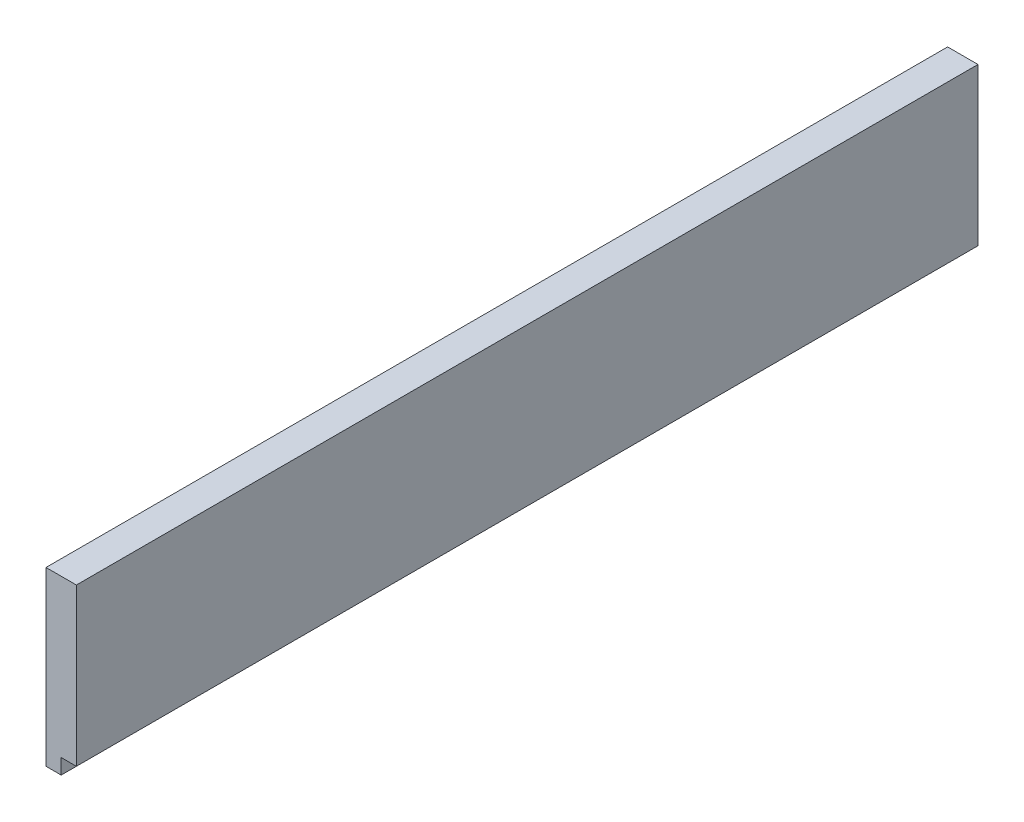
SolidWorks part; units mm, degrees
material "Сосна"
ref_plane "Спереди" through (0, 0, 0) normal (0, 0, 1) x (1, 0, 0)
ref_plane "Сверху" through (0, 0, 0) normal (0, 1, 0) x (1, 0, 0)
ref_plane "Справа" through (0, 0, 0) normal (1, 0, 0) x (0, 0, -1)
sketch "Эскиз1" plane through (0, 0, 0) normal (0, 0, 1) x (1, 0, 0)
  line L0 (0, 0) -> (15, 0)
  line L1 (15, 0) -> (15, 15)
  line L2 (15, 15) -> (30, 15)
  line L3 (30, 15) -> (30, 170)
  line L4 (30, 170) -> (0, 170)
  line L7 (0, 170) -> (0, 0)
  point P3 (44.0891, 21.206)
  dimension "D1" = 155
  dimension "D2" = 30
  dimension "D3" = 15
  dimension "D4" = 15
extrude "Бобышка-Вытянуть1" add sketch "Эскиз1" along normal blind 890
